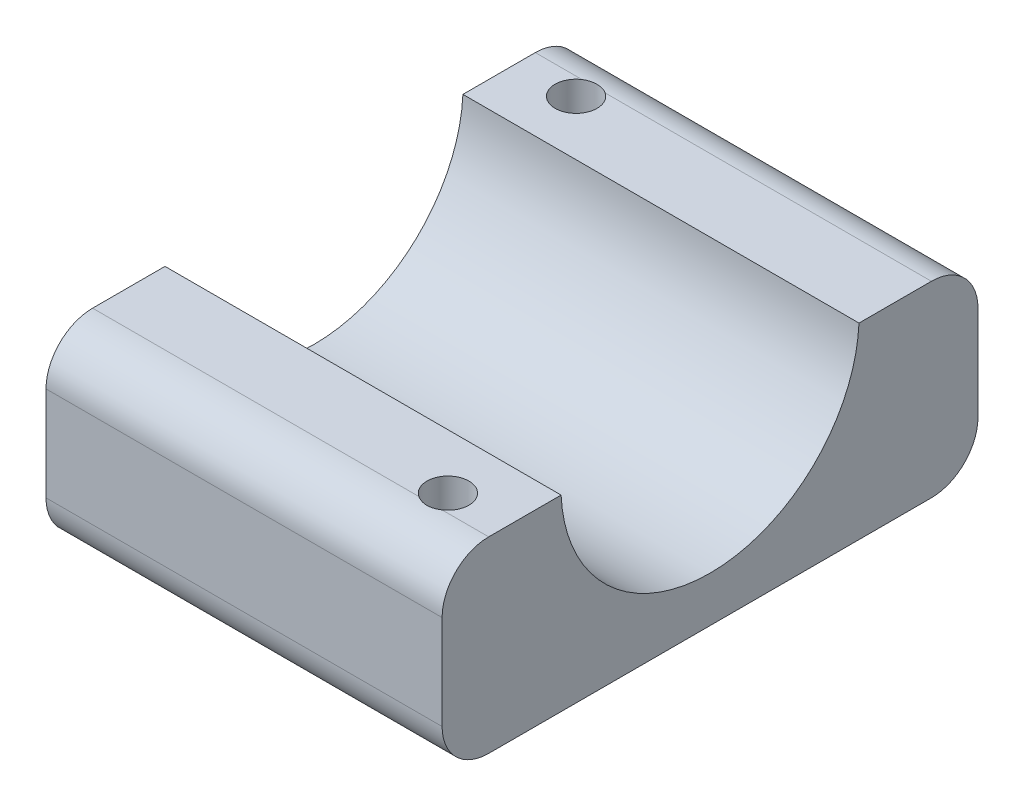
SolidWorks part; units mm, degrees
ref_plane "Front Plane" through (0, 0, 0) normal (0, 0, 1) x (1, 0, 0)
ref_plane "Top Plane" through (0, 0, 0) normal (0, 1, 0) x (1, 0, 0)
ref_plane "Right Plane" through (0, 0, 0) normal (1, 0, 0) x (0, 0, -1)
sketch "Sketch1" plane through (0, 0, 0) normal (1, 0, 0) x (0, 0, -1)
  line L0 (-19, -16.7) -> (19, -16.7)
  line L1 (23, -12.7) -> (23, -4.6)
  line L2 (19, -0.6) -> (-19, -0.6)
  line L3 (-23, -4.6) -> (-23, -12.7)
  arc A0 (19, -16.7) -> (23, -12.7) centre (19, -12.7) ccw
  arc A1 (23, -4.6) -> (19, -0.6) centre (19, -4.6) ccw
  arc A2 (-19, -0.6) -> (-23, -4.6) centre (-19, -4.6) ccw
  arc A3 (-23, -12.7) -> (-19, -16.7) centre (-19, -12.7) ccw
extrude "Boss-Extrude1" add sketch "Sketch1" along normal mid plane 34
sketch "Sketch2" plane through (0, 0, 0) normal (1, 0, 0) x (0, 0, -1)
  circle A0 centre (0, 0) radius 12.8
extrude "Cut-Extrude1" cut sketch "Sketch2" against normal through all and the other way through all
ref_plane "Plane1" through (0, -16.7, 0) normal (0, 1, 0) x (1, 0, 0)
sketch "Sketch3" plane through (0, -16.7, 0) normal (0, 1, 0) x (1, 0, 0)
  circle A0 centre (12, -17.5) radius 1.8
  circle A1 centre (-12, 17.5) radius 1.8
extrude "Cut-Extrude2" cut sketch "Sketch3" along normal blind 17
ref_plane "Plane2" through (0, -16.7, 0) normal (0, 1, 0) x (1, 0, 0)
sketch "Sketch4" plane through (0, -16.7, 0) normal (0, 1, 0) x (1, 0, 0)
  circle A0 centre (12, -17.5) radius 3.25
  circle A1 centre (-12, 17.5) radius 3.25
extrude "Cut-Extrude3" cut sketch "Sketch4" along normal blind 4.3
